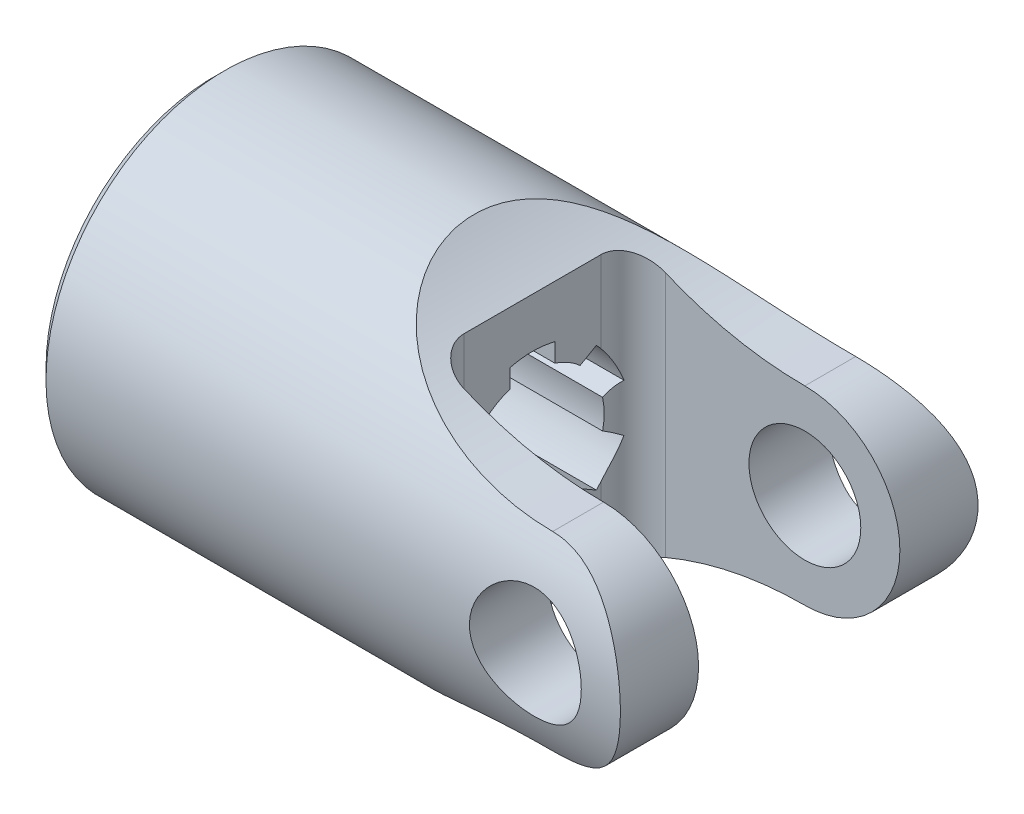
SolidWorks part; units mm, degrees
material "SAE 1145"
ref_plane "Front Plane" through (0, 0, 0) normal (0, 0, 1) x (1, 0, 0)
ref_plane "Top Plane" through (0, 0, 0) normal (0, 1, 0) x (1, 0, 0)
ref_plane "Right Plane" through (0, 0, 0) normal (1, 0, 0) x (0, 0, -1)
sketch "Sketch1" plane through (0, 0, 0) normal (1, 0, 0) x (0, 0, -1)
  circle A0 centre (0, 0) radius 25.4
  dimension "D1" = 50.8
extrude "Boss-Extrude1" add sketch "Sketch1" along normal blind 83.0898
sketch "Sketch4" plane through (0, 0, 0) normal (0, 0, 1) x (1, 0, 0)
  line L0 (0, 0) -> (100.3708, 0) construction
  line L1 (0, 25.4) -> (0, -25.4) construction
  line L2 (83.0898, -25.4) -> (83.0898, 25.4)
  line L3 (83.0898, -25.4) -> (83.0898, 25.4) construction
  line L4 (0, -25.4) -> (83.0898, -25.4) construction
  line L5 (36.917, -25.4) -> (83.0898, -25.4)
  line L6 (83.0898, 25.4) -> (0, 25.4) construction
  line L7 (36.917, 25.4) -> (83.0898, 25.4)
  arc A0 (69.596, 13.4937) -> (69.596, -13.4937) centre (69.596, 0) cw
  arc A1 (69.596, -13.4937) -> (36.917, -25.4) centre (69.596, -64.2938) ccw
  arc A2 (69.596, 13.4937) -> (36.917, 25.4) centre (69.596, 64.2938) cw
  dimension "D1" = 13.4937
  dimension "D2" = 50.8
  dimension "D3" = 50.8
extrude "Cut-Extrude1" cut sketch "Sketch4" against normal mid plane 87.376 contours A2 A0 L2 L7 | A0 A1 L5 L2
sketch "Sketch5" plane through (0, 0, 0) normal (0, 0, 1) x (1, 0, 0)
  circle A0 centre (69.596, 0) radius 7.9426
  dimension "D1" = 15.8852
extrude "Cut-Extrude2" cut sketch "Sketch5" against normal mid plane 87.376
sketch "Sketch6" plane through (0, 0, 0) normal (0, 1, 0) x (1, 0, 0)
  line L0 (69.596, 32.1437) -> (69.596, -33.5748)
  line L1 (83.0898, -14.2938) -> (83.0898, 14.2939)
  line L2 (83.0898, -25.4) -> (83.0898, 25.4) construction
  line L3 (83.0898, 14.2939) -> (49.784, 14.2938)
  line L4 (45.212, 9.7218) -> (45.212, -9.7218)
  line L5 (49.784, -14.2938) -> (83.0898, -14.2938)
  line L6 (0, 0) -> (97.1359, 0) construction
  arc A0 (49.784, 14.2938) -> (45.212, 9.7218) centre (49.784, 9.7218) ccw
  arc A1 (45.212, -9.7218) -> (49.784, -14.2938) centre (49.784, -9.7218) ccw
  point P15 (45.212, 0)
  dimension "D2" = 4.572
  dimension "D3" = 4.572
  dimension "D1" = 24.384
  dimension "D4" = 28.5877
extrude "Cut-Extrude3" cut sketch "Sketch6" against normal mid plane 87.376 contours L4 L6 L0 L3 A0 | L6 L4 A1 L5 L0 | L6 L0 L5 L1 | L0 L6 L1 L3
chamfer "Chamfer1" distance 1.524 angle 45 1 edges at (0, 0, -25.4)
sketch "Sketch8" plane through (0, 0, 0) normal (-1, 0, 0) x (0, 0, 1)
  circle A0 centre (0, 0) radius 10.16
  dimension "D1" = 20.32
extrude "Cut-Extrude4" cut sketch "Sketch8" against normal through all
sketch "Sketch7" plane through (0, 0, 0) normal (-1, 0, 0) x (0, 0, 1)
  line L0 (-25.4, 0) -> (23.876, 0) construction
  line L1 (0, 25.4) -> (0, -25.4) construction
  line L4 (-3.175, 9.6512) -> (-3.175, 12.2967)
  line L6 (3.175, 9.6512) -> (3.175, 12.2967)
  circle A0 centre (0, 0) radius 25.4 construction
  circle A1 centre (0, 0) radius 23.876 construction
  arc A2 (3.175, 12.2967) -> (-3.175, 12.2967) centre (0, 0) ccw
  circle A3 centre (0, 0) radius 10.16 construction
  arc A5 (3.175, 9.6512) -> (-3.175, 9.6512) centre (0, 0) ccw
  dimension "D1" = 6.35
  dimension "1" = 25.4
extrude "Cut-Extrude5" cut sketch "Sketch7" against normal through all
pattern_circular "CirPattern1" count 6 over 360 about axis through (0, 0, 0) along (1, 0, 0) of "Cut-Extrude5"
